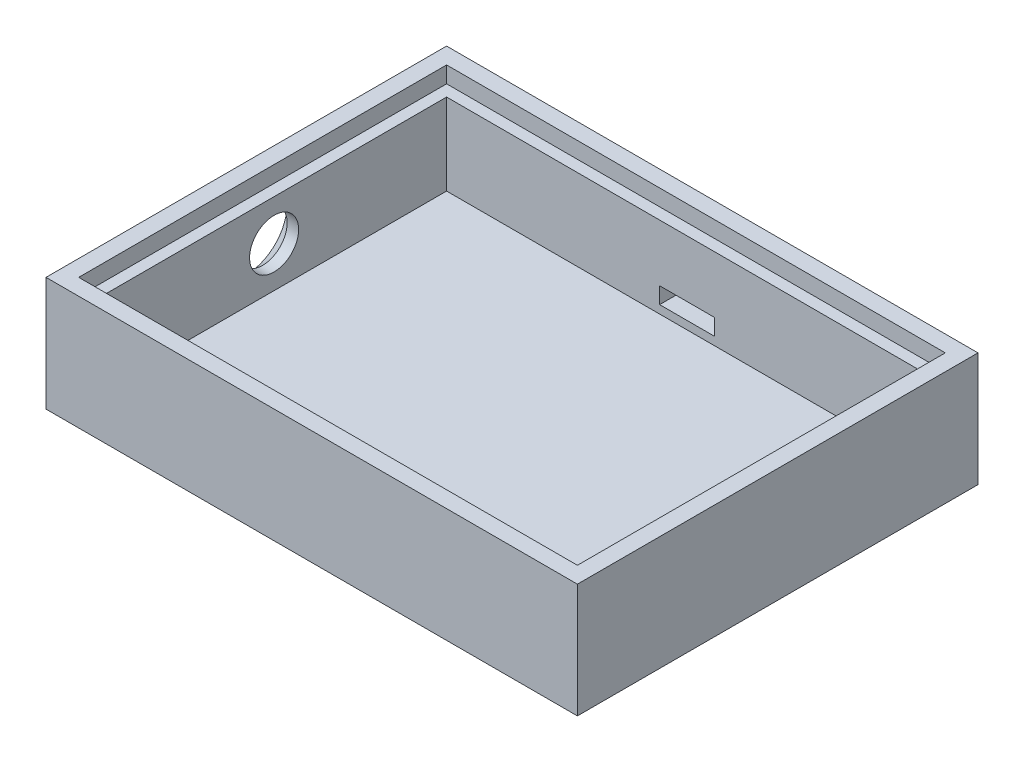
SolidWorks part; units mm, degrees
ref_plane "Front Plane" through (0, 0, 0) normal (0, 0, 1) x (1, 0, 0)
ref_plane "Top Plane" through (0, 0, 0) normal (0, 1, 0) x (1, 0, 0)
ref_plane "Right Plane" through (0, 0, 0) normal (1, 0, 0) x (0, 0, -1)
sketch "Sketch1" plane through (0, 0, 0) normal (0, 1, 0) x (1, 0, 0)
  line L0 (0, 0) -> (0, 122.5) construction
  line L1 (-162.5, 122.5) -> (162.5, 122.5)
  line L2 (-162.5, 122.5) -> (-162.5, -122.5)
  line L3 (-162.5, -122.5) -> (162.5, -122.5)
  line L4 (162.5, 122.5) -> (162.5, -122.5)
  line L5 (0, 0) -> (162.5, 0) construction
  dimension "D1" = 325
  dimension "D2" = 245
extrude "Boss-Extrude1" add sketch "Sketch1" along normal blind 10
sketch "Sketch2" plane through (0, 10, 0) normal (0, 1, 0) x (1, 0, 0)
  line L0 (162.5, 122.5) -> (-162.5, 122.5) construction
  line L1 (162.5, 122.5) -> (-162.5, 122.5)
  line L2 (-162.5, 122.5) -> (-162.5, -122.5) construction
  line L3 (-162.5, 122.5) -> (-162.5, -122.5)
  line L4 (-162.5, -122.5) -> (162.5, -122.5) construction
  line L5 (-162.5, -122.5) -> (162.5, -122.5)
  line L6 (162.5, -122.5) -> (162.5, 122.5) construction
  line L7 (162.5, -122.5) -> (162.5, 122.5)
  line L8 (145.5, 105.5) -> (-145.5, 105.5)
  line L9 (-145.5, 105.5) -> (-145.5, -105.5)
  line L10 (-145.5, -105.5) -> (145.5, -105.5)
  line L11 (145.5, -105.5) -> (145.5, 105.5)
  dimension "D1" = 17
extrude "Boss-Extrude2" add sketch "Sketch2" along normal blind 49.8
sketch "Sketch3" plane through (0, 59.8, 0) normal (0, 1, 0) x (1, 0, 0)
  line L0 (-162.5, -122.5) -> (162.5, -122.5) construction
  line L1 (162.5, -122.5) -> (162.5, 122.5) construction
  line L2 (162.5, 122.5) -> (-162.5, 122.5) construction
  line L3 (-162.5, 122.5) -> (-162.5, -122.5) construction
  line L4 (-162.5, -122.5) -> (162.5, -122.5)
  line L5 (162.5, -122.5) -> (162.5, 122.5)
  line L6 (162.5, 122.5) -> (-162.5, 122.5)
  line L7 (-162.5, 122.5) -> (-162.5, -122.5)
  line L8 (-152.5, -112.5) -> (152.5, -112.5)
  line L9 (152.5, -112.5) -> (152.5, 112.5)
  line L10 (152.5, 112.5) -> (-152.5, 112.5)
  line L11 (-152.5, 112.5) -> (-152.5, -112.5)
  dimension "D1" = 10
extrude "Boss-Extrude3" add sketch "Sketch3" along normal blind 10
sketch "Sketch4" plane through (-162.5, 0, 0) normal (-1, 0, 0) x (0, 0, 1)
  line L0 (-122.5, 34.9) -> (122.5, 34.9) construction
  line L1 (-122.5, 69.8) -> (-122.5, 0) construction
  line L2 (122.5, 69.8) -> (122.5, 0) construction
  circle A0 centre (0, 34.9) radius 15
  point P8 (0, 0)
  point P9 (0, 0)
  point P10 (0, 0)
  point P11 (0, 0)
  dimension "D1" = 30
extrude "Cut-Extrude1" cut sketch "Sketch4" against normal blind 30
chamfer "Chamfer1" distance 10 angle 45 1 edges at (-162.5, 34.9, 15)
sketch "Sketch5" plane through (0, 0, -105.5) normal (0, 0, 1) x (1, 0, 0)
  line L0 (145.5, 10) -> (-145.5, 10) construction
  line L1 (-10.5, 25) -> (13.5, 25)
  line L2 (-10.5, 25) -> (-10.5, 15)
  line L3 (-10.5, 15) -> (13.5, 15)
  line L4 (13.5, 25) -> (13.5, 15)
  line L5 (-145.5, 59.8) -> (-145.5, 10) construction
  dimension "D1" = 5
  dimension "D2" = 24
  dimension "D3" = 10
  dimension "D4" = 135
extrude "Cut-Extrude2" cut sketch "Sketch5" against normal through all
sketch "Sketch6" plane through (0, 0, -105.5) normal (0, 0, 1) x (1, 0, 0)
  line L0 (-10.5, 15) -> (13.5, 15) construction
  line L1 (-15.2, 25) -> (18.2, 25)
  line L2 (-15.2, 25) -> (-15.2, 15)
  line L3 (-15.2, 15) -> (18.2, 15)
  line L4 (18.2, 25) -> (18.2, 15)
  line L5 (13.5, 25) -> (-10.5, 25) construction
  line L7 (1.5, 25) -> (1.5, 15) construction
  line L8 (1.5, 25) -> (1.5, 15) construction
  point P12 (0, 0)
  dimension "D1" = 33.4
extrude "Cut-Extrude3" cut sketch "Sketch6" against normal blind 10
